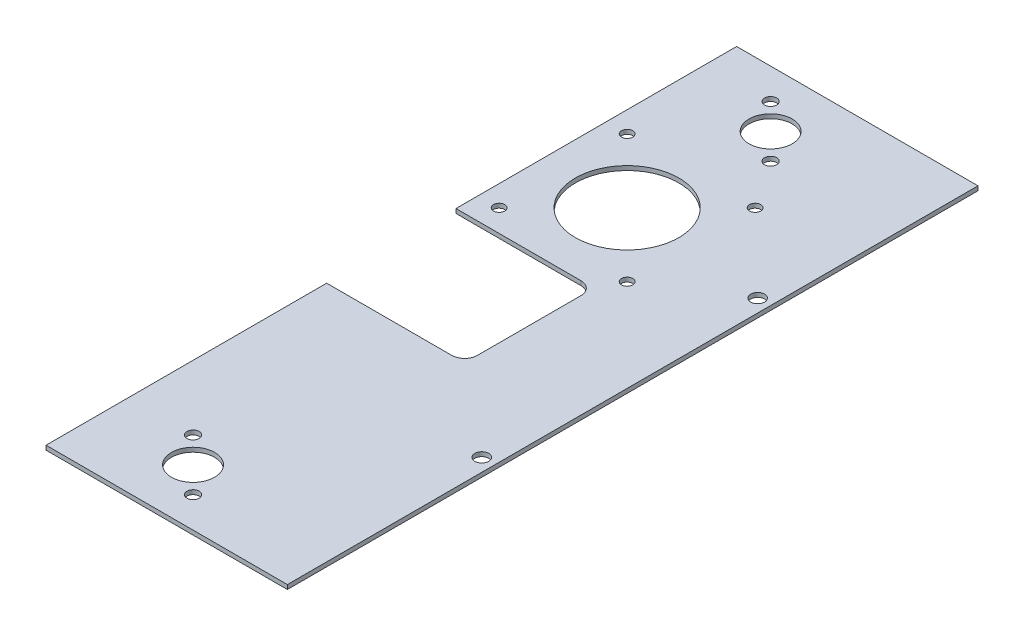
SolidWorks part; units mm, degrees
ref_plane "Front Plane" through (0, 0, 0) normal (0, 0, 1) x (1, 0, 0)
ref_plane "Top Plane" through (0, 0, 0) normal (0, 1, 0) x (1, 0, 0)
ref_plane "Right Plane" through (0, 0, 0) normal (1, 0, 0) x (0, 0, -1)
sketch "Sketch1" plane through (0, 0, 0) normal (0, 1, 0) x (1, 0, 0)
  line L0 (-22.1867, -110.036) -> (-22.1867, -213.414)
  line L1 (-22.1867, 40.967) -> (66.7133, 40.967)
  line L2 (-22.1867, 40.967) -> (-22.1867, -62.411)
  line L3 (-22.1867, -213.414) -> (66.7133, -213.414)
  line L4 (66.7133, 40.967) -> (66.7133, -213.414)
  line L5 (-22.1867, -62.411) -> (23.8508, -62.411)
  line L6 (9.1061, -30.661) -> (-15.3326, -30.661) construction
  line L7 (-22.1867, -110.036) -> (23.8508, -110.036)
  line L8 (28.6133, -67.1735) -> (28.6133, -105.2735)
  line L9 (9.1061, -30.661) -> (9.1061, -4.5218) construction
  arc A0 (23.8508, -110.036) -> (28.6133, -105.2735) centre (23.8508, -105.2735) ccw
  arc A1 (23.8508, -62.411) -> (28.6133, -67.1735) centre (23.8508, -67.1735) cw
  circle A2 centre (9.1061, -30.661) radius 19.05
  circle A3 centre (11.1508, 20.139) radius 7.9375
  circle A4 centre (11.1508, -192.586) radius 7.9375
  circle A5 centre (-14.4651, -7.0898) radius 2.0621
  circle A6 centre (32.6773, -7.0898) radius 2.0621
  circle A7 centre (32.6773, -54.2322) radius 2.0621
  circle A8 centre (-14.4651, -54.2322) radius 2.0621
  point P12 (28.6133, -62.411)
  dimension "D6" = 4.7625
  dimension "D8" = 19.5072
  dimension "D9" = 38.1
  dimension "D10" = 15.875
  dimension "D11" = 17.4625
  dimension "D12" = 50.8
  dimension "D13" = 15.875
  dimension "D14" = 17.4625
  dimension "D15" = 82.55
  dimension "D1" = 88.9
  dimension "D2" = 254.381
  dimension "D3" = 103.378
  dimension "D4" = 151.003
  dimension "D5" = 50.8
  dimension "D7" = 31.75
  dimension "D16" = 47.1424
  dimension "D17" = 47.1424
extrude "Boss-Extrude1" add sketch "Sketch1" along normal blind 1.5875
hole_wizard "#10 Clearance Hole1" positions "Sketch6" profile "Sketch4" hole size "#10" standard "ANSI Inch" end condition through all
sketch "Sketch6" plane through (0, 1.5875, 0) normal (0, 1, 0) x (1, 0, 0)
  line L1 (28.6133, -67.1735) -> (28.6133, -105.2735) construction
  line L3 (28.6133, -86.2235) -> (84.9185, -86.2235) construction
  line L6 (66.7133, -213.414) -> (66.7133, 40.967) construction
  point P0 (61.9508, -137.0235)
  point P22 (61.9508, -35.4235)
  dimension "D1" = 101.6
  dimension "D2" = 4.7625
sketch "Sketch4" plane through (61.9508, 1.5875, 137.0235) normal (1, 0, 0) x (0, 0, 1)
  line L0 (0, 0) -> (0, 1.5875)
  line L1 (0, 1.5875) -> (2.5527, 1.5875)
  line L2 (2.5527, 1.5875) -> (2.5527, 0)
  line L5 (2.5527, 0) -> (0, 0)
  line L11 (0, -6.35) -> (0, 107.95) construction
  dimension "Thru Hole Dia." = 5.1054
  dimension "Thru Hole Depth" = 1.5875
hole_wizard "#8 Clearance Hole1" positions "Sketch8" profile "Sketch7" hole size "#8" standard "ANSI Inch"
sketch "Sketch8" plane through (0, 1.5875, 0) normal (0, 1, 0) x (1, 0, 0)
  circle A0 centre (11.1508, 20.139) radius 7.9375 construction
  circle A1 centre (11.1508, -192.586) radius 7.9375 construction
  point P0 (1.6258, 29.664)
  point P2 (20.6758, 10.614)
  point P7 (1.6258, -183.061)
  point P9 (20.6758, -202.111)
  dimension "D7" = 9.525
  dimension "D1" = 9.525
  dimension "D2" = 9.525
  dimension "D3" = 9.525
  dimension "D4" = 9.525
  dimension "D5" = 9.525
  dimension "D6" = 9.525
  dimension "D8" = 9.525
sketch "Sketch7" plane through (1.6258, 1.5875, -29.664) normal (1, 0, 0) x (0, 0, 1)
  line L0 (0, 0) -> (0, 7.7007)
  line L1 (0, 7.7007) -> (2.2479, 6.35)
  line L2 (2.2479, 6.35) -> (2.2479, 0)
  line L5 (2.2479, 0) -> (0, 0)
  line L10 (0, 7.7007) -> (-2.2479, 6.35) construction
  line L11 (0, -6.35) -> (0, 107.95) construction
  dimension "Hole Dia." = 4.4958
  dimension "Hole Depth" = 6.35
  dimension "Drill Angle" = 118
